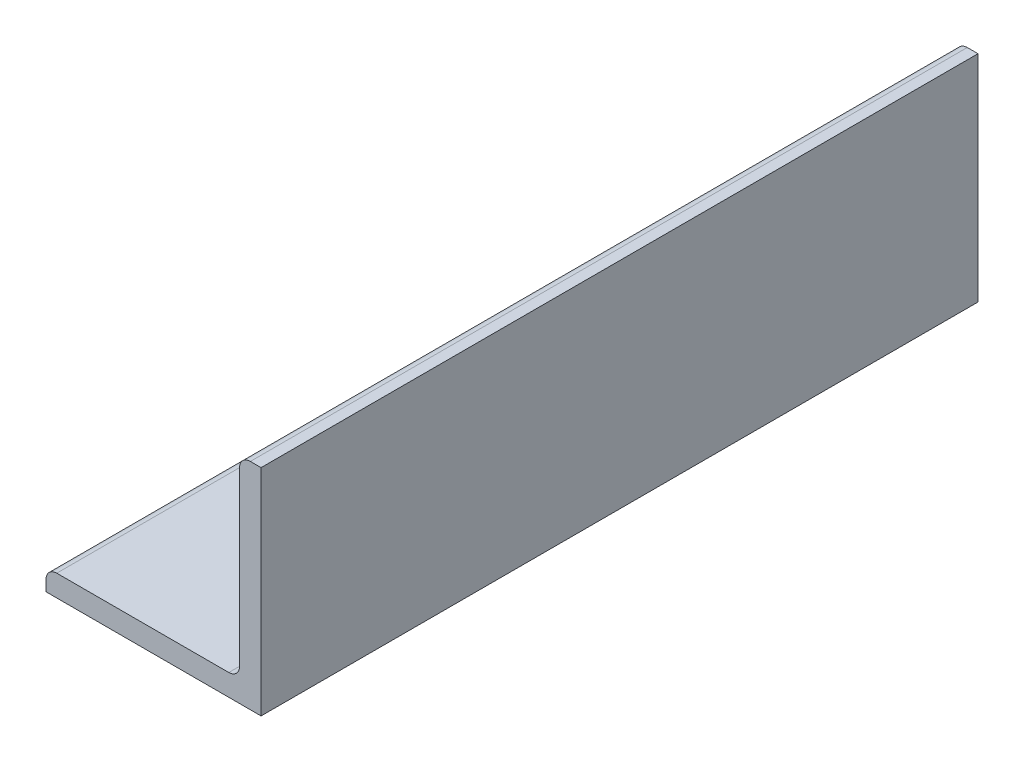
SolidWorks part; units mm, degrees
material "ASTM A36 Steel"
ref_plane "Front Plane" through (0, 0, 0) normal (0, 0, 1) x (1, 0, 0)
ref_plane "Top Plane" through (0, 0, 0) normal (0, 1, 0) x (1, 0, 0)
ref_plane "Right Plane" through (0, 0, 0) normal (1, 0, 0) x (0, 0, -1)
sketch "Sketch1" plane through (0, 0, 0) normal (0, 0, 1) x (1, 0, 0)
  line L0 (-135.6009, 27) -> (-135.6009, -3)
  line L1 (-135.6009, -3) -> (-165.6009, -3)
  line L2 (-165.6009, -3) -> (-165.6009, -1.5)
  line L3 (-164.1009, 0) -> (-140.1009, 0)
  line L4 (-138.6009, 1.5) -> (-138.6009, 25.5)
  line L5 (-137.1009, 27) -> (-135.6009, 27)
  arc A0 (-138.6009, 25.5) -> (-137.1009, 27) centre (-137.1009, 25.5) cw
  arc A1 (-140.1009, 0) -> (-138.6009, 1.5) centre (-140.1009, 1.5) ccw
  arc A2 (-165.6009, -1.5) -> (-164.1009, 0) centre (-164.1009, -1.5) cw
  point P9 (-138.6009, 27)
  point P14 (-165.6009, 0)
  dimension "D5" = 1.5
  dimension "D1" = 3
  dimension "D2" = 30
  dimension "D3" = 30
  dimension "D4" = 3
extrude "Boss-Extrude1" add sketch "Sketch1" along normal blind 100
